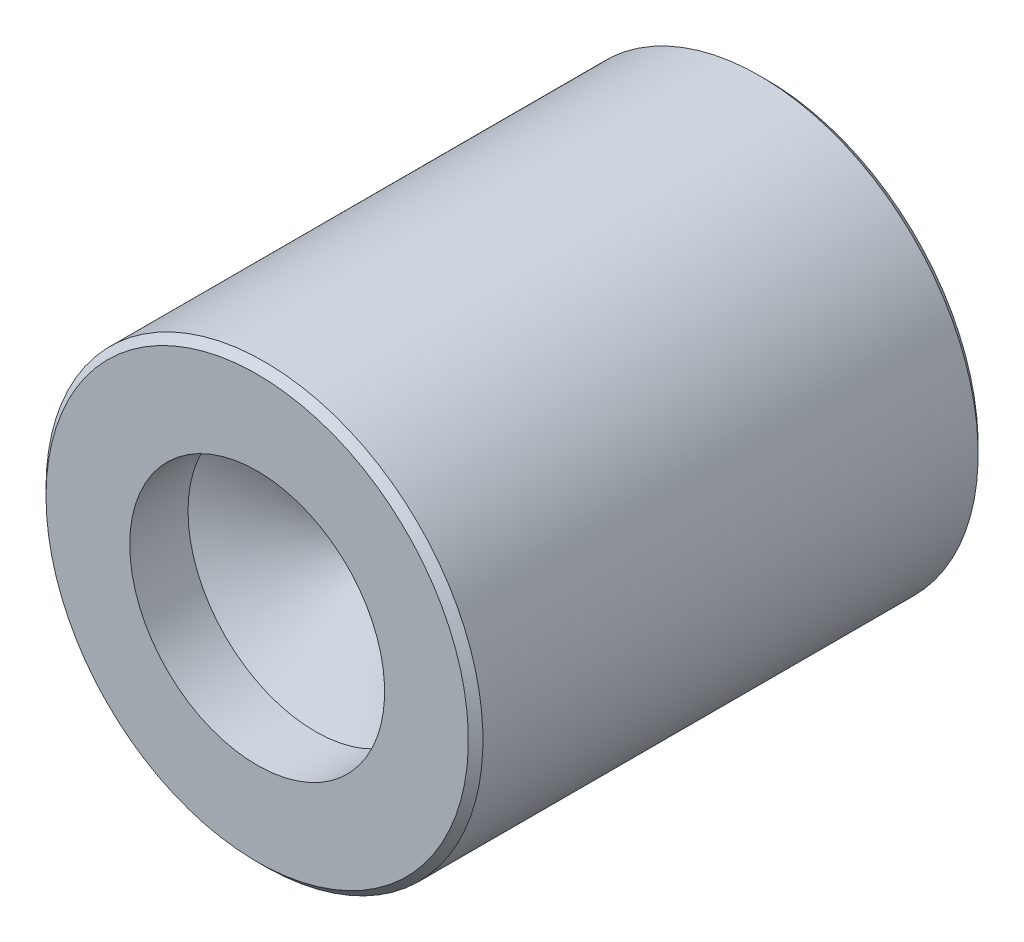
SolidWorks part; units mm, degrees
ref_plane "Plan de face" through (0, 0, 0) normal (0, 0, 1) x (1, 0, 0)
ref_plane "Plan de dessus" through (0, 0, 0) normal (0, 1, 0) x (1, 0, 0)
ref_plane "Plan de droite" through (0, 0, 0) normal (1, 0, 0) x (0, 0, -1)
ref_plane "Plan1" through (0, 0, 0) normal (0, -1, 0) x (1, 0, 0)
sketch "Esquisse1" plane through (0, 0, 0) normal (0, -1, 0) x (1, 0, 0)
  line L0 (16.7708, 59.4167) -> (0, 49.3397)
  line L1 (0, 49.3397) -> (0, 0)
  line L2 (0, 0) -> (27.7917, 0)
  line L3 (27.7917, 0) -> (28.75, 0.9583)
  line L4 (28.75, 0.9583) -> (28.75, 66.125)
  line L5 (28.75, 66.125) -> (27.7917, 67.0833)
  line L6 (27.7917, 67.0833) -> (16.7708, 67.0833)
  line L7 (16.7708, 67.0833) -> (16.7708, 59.4167)
  line L8 (0, 67.0833) -> (0, 0) construction
  dimension "D1" = 57.5
revolve "Révolution1" add sketch "Esquisse1" angle 360 about L8
